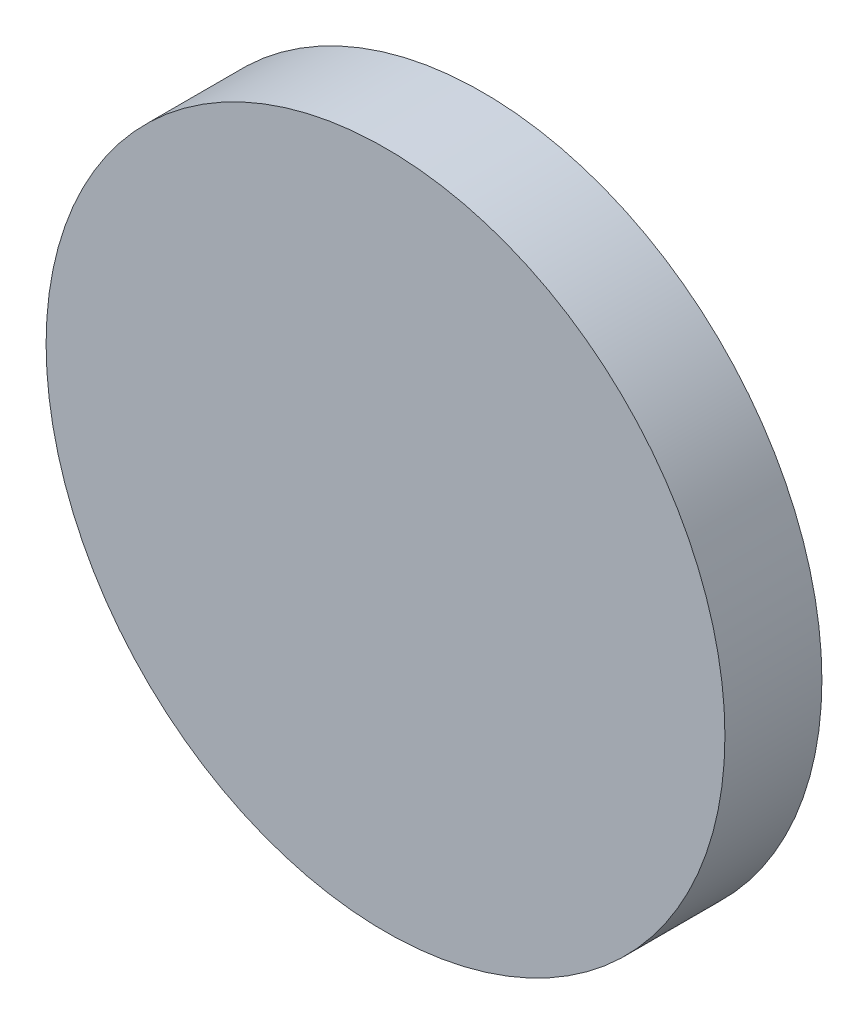
SolidWorks part; units mm, degrees
material "Acrylic (Medium-high impact)"
ref_plane "Front Plane" through (0, 0, 0) normal (0, 0, 1) x (1, 0, 0)
ref_plane "Top Plane" through (0, 0, 0) normal (0, 1, 0) x (1, 0, 0)
ref_plane "Right Plane" through (0, 0, 0) normal (1, 0, 0) x (0, 0, -1)
sketch "Sketch1" plane through (0, 0, 0) normal (0, 0, 1) x (1, 0, 0)
  circle A0 centre (0, 0) radius 22.225
  dimension "D1" = 44.45
extrude "Boss-Extrude1" add sketch "Sketch1" along normal blind 6.35
